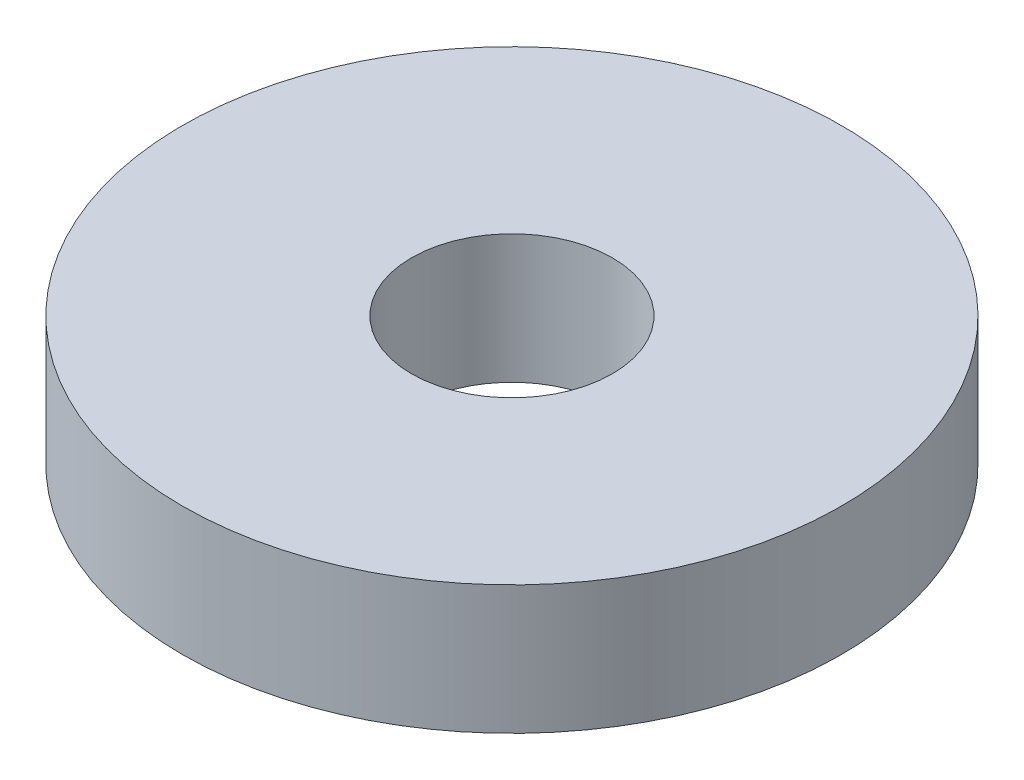
SolidWorks part; units mm, degrees
material "PTFE (general)"
ref_plane "Ön Düzlem" through (0, 0, 0) normal (0, 0, 1) x (1, 0, 0)
ref_plane "Üst Düzlem" through (0, 0, 0) normal (0, 1, 0) x (1, 0, 0)
ref_plane "Sağ Düzlem" through (0, 0, 0) normal (1, 0, 0) x (0, 0, -1)
sketch "Sketch1" plane through (0, 0, 0) normal (0, 1, 0) x (1, 0, 0)
  circle A0 centre (0, 0) radius 0.625
  circle A1 centre (0, 0) radius 2.05
  dimension "D1" = 1.25
  dimension "D2" = 4.1
extrude "Boss-Extrude1" add sketch "Sketch1" along normal blind 0.8
